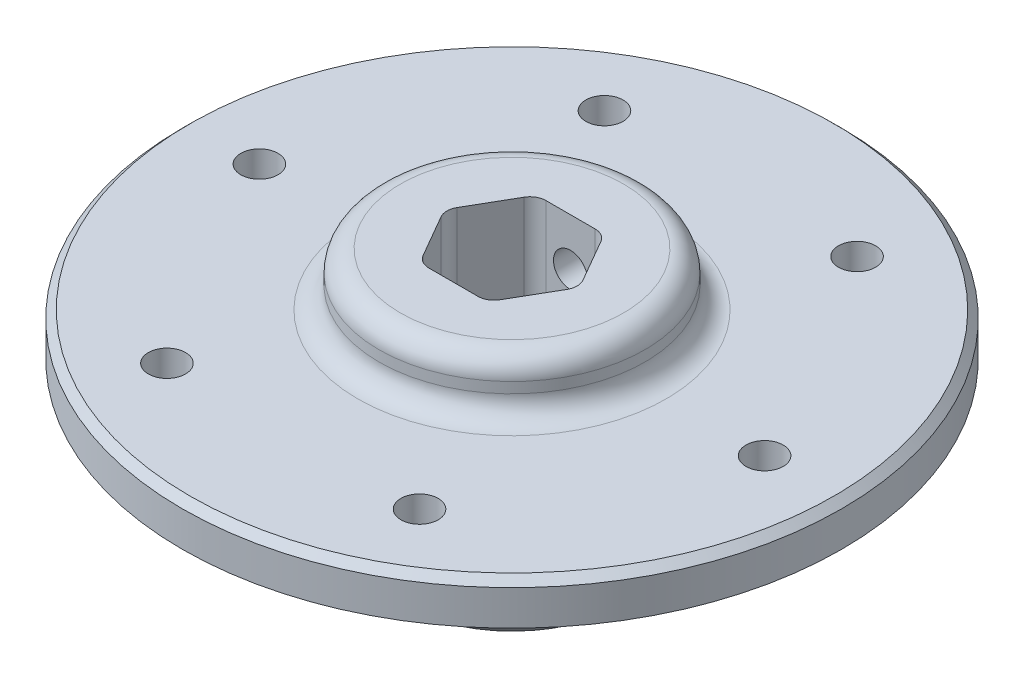
SolidWorks part; units mm, degrees
material "Cast Alloy Steel"
ref_plane "Front" through (0, 0, 0) normal (0, 0, 1) x (1, 0, 0)
ref_plane "Top" through (0, 0, 0) normal (0, 1, 0) x (1, 0, 0)
ref_plane "Right" through (0, 0, 0) normal (1, 0, 0) x (0, 0, -1)
sketch "Sketch1" plane through (0, 0, 0) normal (0, 1, 0) x (1, 0, 0)
  line L0 (0, 0) -> (0, 23.75) construction
  line L1 (0, 0) -> (-11.875, 20.5681) construction
  circle A7 centre (0, 0) radius 31
  circle A9 centre (0, 0) radius 23.75 construction
  circle A10 centre (-11.875, 20.5681) radius 1.75
  circle A11 centre (11.875, 20.5681) radius 1.75
  circle A12 centre (23.75, 0) radius 1.75
  circle A13 centre (11.875, -20.5681) radius 1.75
  circle A14 centre (-11.875, -20.5681) radius 1.75
  circle A15 centre (-23.75, 0) radius 1.75
  point P19 (0, 0)
  dimension "D1" = 47.5
  dimension "D2" = 30
  dimension "D4" = 62
  dimension "D3" = 3.5
extrude "Boss-Extrude1" add sketch "Sketch1" along normal blind 4
sketch "Sketch2" plane through (0, 4, 0) normal (0, 1, 0) x (1, 0, 0)
  circle A0 centre (0, 0) radius 12.5
  dimension "D1" = 25
extrude "Boss-Extrude2" add sketch "Sketch2" along normal blind 5
sketch "Sketch3" plane through (0, 9, 0) normal (0, 1, 0) x (1, 0, 0)
  line L0 (0, 0) -> (12.5, 0) construction
  line L1 (3.1754, 5.5) -> (-3.1754, 5.5)
  line L2 (-3.1754, 5.5) -> (-6.3509, 0)
  line L3 (-6.3509, 0) -> (-3.1754, -5.5)
  line L4 (-3.1754, -5.5) -> (3.1754, -5.5)
  line L5 (3.1754, -5.5) -> (6.3509, 0)
  line L6 (6.3509, 0) -> (3.1754, 5.5)
  circle A0 centre (0, 0) radius 5.5 construction
  circle A1 centre (0, 0) radius 12.5 construction
  dimension "D1" = 11
extrude "Cut-Extrude1" cut sketch "Sketch3" against normal through all
fillet "Fillet1" radius 2 6 edges at (3.1754, 4.5, 5.5) (-3.1754, 4.5, 5.5) (3.1754, 4.5, -5.5) (6.3509, 4.5, 0) (-6.3509, 4.5, 0) (-3.1754, 4.5, -5.5)
fillet "Fillet2" radius 2 2 edges at (0, 4, 12.5) (0, 9, 12.5)
sketch "Sketch4" plane through (0, 9, 0) normal (0, 1, 0) x (1, 0, 0)
  line L0 (0, 0) -> (0, 12.5) construction
  circle A0 centre (0, 0) radius 12.5 construction
ref_plane "Plane1" through (0, 9, -12.5) normal (0, 0, -1) x (-1, 0, 0)
sketch "Sketch5" plane through (0, 9, -12.5) normal (0, 0, -1) x (-1, 0, 0)
  line L0 (12.5, -2) -> (-12.5, -2) construction
  circle A0 centre (0, -4.5) radius 1.6
  dimension "D1" = 3.2
  dimension "D2" = 2.5
extrude "Cut-Extrude2" cut sketch "Sketch5" against normal blind 10
chamfer "Chamfer2" distance 0.7 angle 45 1 edges at (0, 4, 31)
sketch "Sketch6" plane through (0, 0, 0) normal (0, -1, 0) x (-1, 0, 0)
  circle A0 centre (0, 0) radius 11.5
  dimension "D1" = 23
extrude "Boss-Extrude3" add sketch "Sketch6" along normal blind 15
fillet "Fillet3" radius 2 1 edges at (0, -15, -11.5)
sketch "Sketch7" plane through (0, -15, 0) normal (0, -1, 0) x (-1, 0, 0)
  line L0 (0, 0) -> (-9.5, 0) construction
  line L1 (-3.1754, -5.5) -> (3.1754, -5.5)
  line L2 (3.1754, -5.5) -> (6.3509, 0)
  line L3 (6.3509, 0) -> (3.1754, 5.5)
  line L4 (3.1754, 5.5) -> (-3.1754, 5.5)
  line L5 (-3.1754, 5.5) -> (-6.3509, 0)
  line L6 (-6.3509, 0) -> (-3.1754, -5.5)
  circle A0 centre (0, 0) radius 5.5 construction
  circle A1 centre (0, 0) radius 9.5 construction
  dimension "D1" = 11
extrude "Cut-Extrude3" cut sketch "Sketch7" against normal through all
fillet "Fillet4" radius 1.5 6 edges at (3.1754, -3, -5.5) (-6.3509, -3, 0) (-3.1754, -3, 5.5) (3.1754, -3, 5.5) (6.3509, -3, 0) (-3.1754, -3, -5.5)
